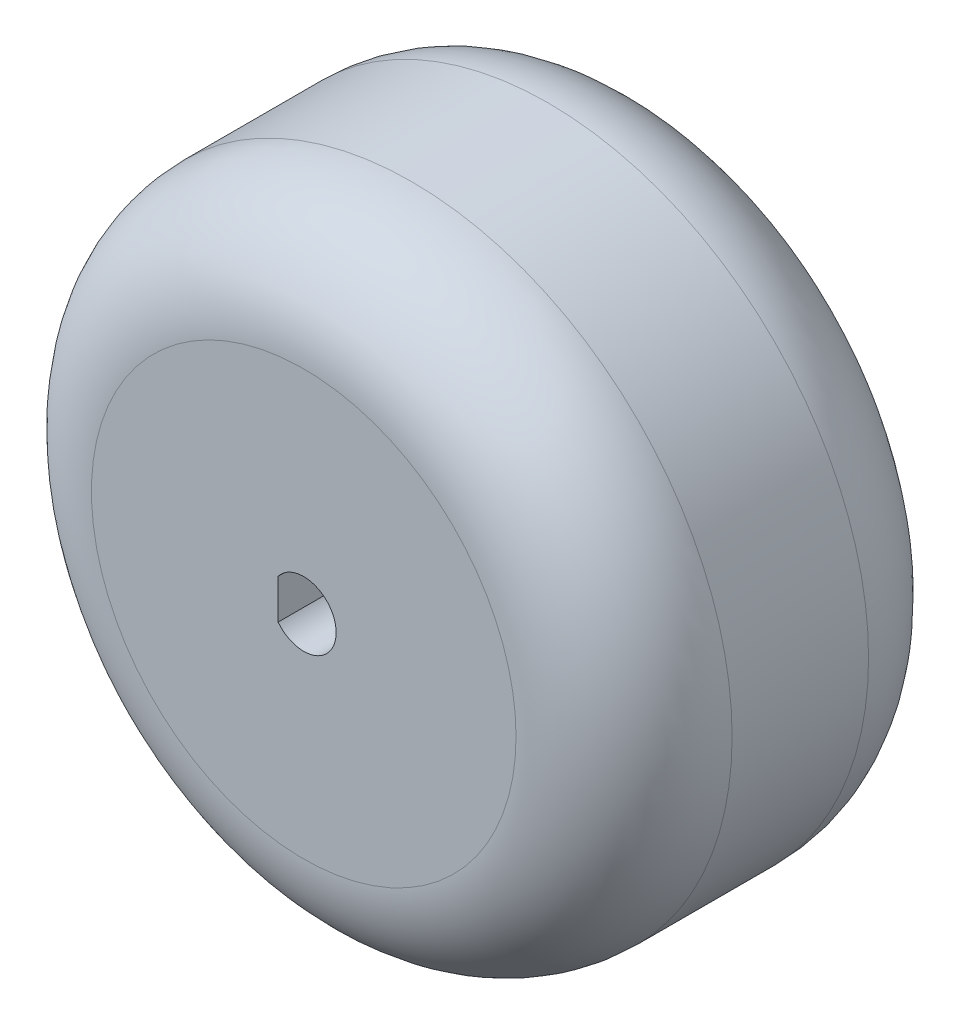
SolidWorks part; units mm, degrees
ref_plane "Plan de face" through (0, 0, 0) normal (0, 0, 1) x (1, 0, 0)
ref_plane "Plan de dessus" through (0, 0, 0) normal (0, 1, 0) x (1, 0, 0)
ref_plane "Plan de droite" through (0, 0, 0) normal (1, 0, 0) x (0, 0, -1)
sketch "Esquisse1" plane through (0, 0, 0) normal (0, 0, 1) x (1, 0, 0)
  circle A0 centre (-8.872, 11.1616) radius 29.65
  dimension "D1" = 59.3
extrude "Boss.-Extru.1" add sketch "Esquisse1" along normal blind 32.63
sketch "Esquisse3" plane through (0, 0, 32.63) normal (0, 0, 1) x (1, 0, 0)
  circle A0 centre (-8.872, 11.1616) radius 3
  circle A1 centre (-8.872, 11.1616) radius 29.65 construction
  dimension "D1" = 0
extrude "Enlèv. mat.-Extru.1" cut sketch "Esquisse3" against normal blind 33.63
sketch "Esquisse4" plane through (0, 0, 32.63) normal (0, 0, 1) x (1, 0, 0)
  line L1 (-13.9396, 14.0207) -> (-11.242, 14.0207)
  line L2 (-13.9396, 14.0207) -> (-13.9396, 8.0534)
  line L3 (-13.9396, 8.0534) -> (-11.242, 8.0534)
  line L4 (-11.242, 14.0207) -> (-11.242, 8.0534)
  circle A0 centre (-8.872, 11.1616) radius 3 construction
  dimension "D1" = 2.37
extrude "Boss.-Extru.4" add sketch "Esquisse4" against normal blind 32.63
fillet "Congé1" radius 10 1 edges at (20.778, 11.1616, 0)
fillet "Congé2" radius 10 1 edges at (20.778, 11.1616, 32.63)
